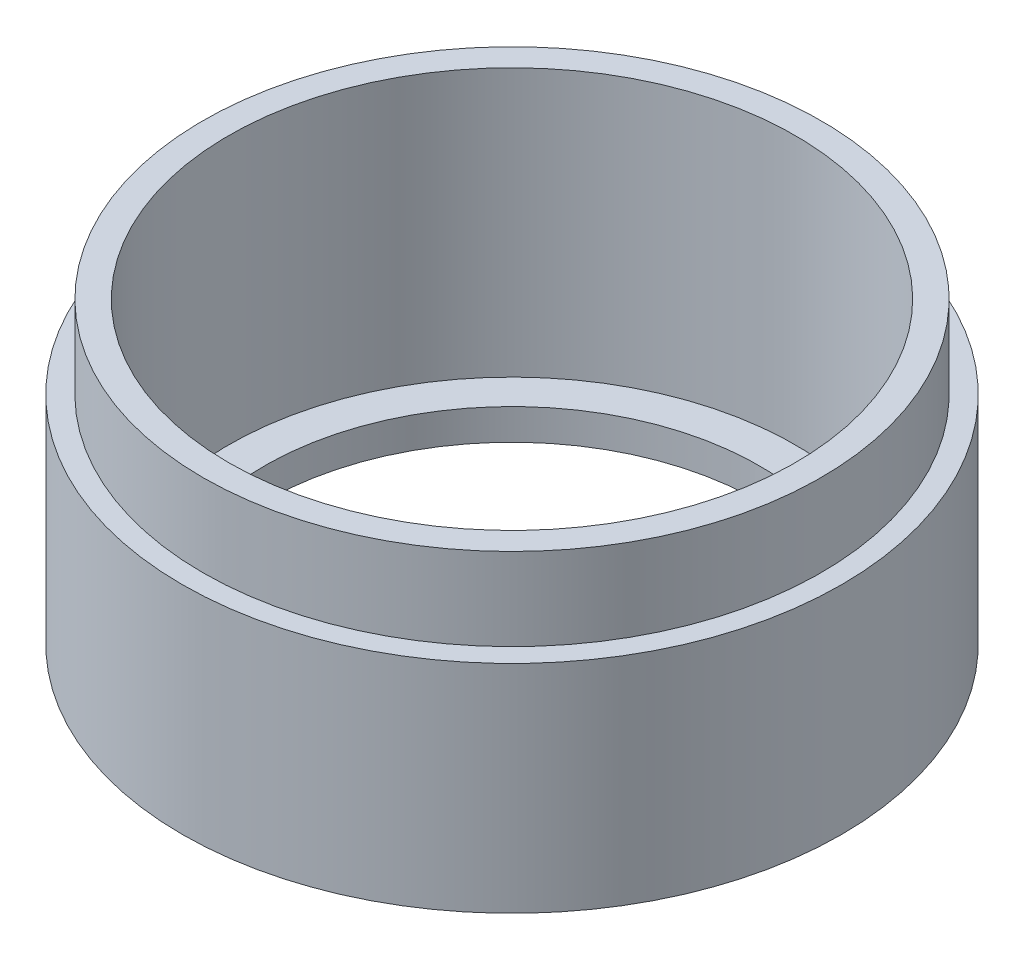
SolidWorks part; units mm, degrees
ref_plane "Спереди" through (0, 0, 0) normal (0, 0, 1) x (1, 0, 0)
ref_plane "Сверху" through (0, 0, 0) normal (0, 1, 0) x (1, 0, 0)
ref_plane "Справа" through (0, 0, 0) normal (1, 0, 0) x (0, 0, -1)
sketch "Эскиз1" plane through (0, 0, 0) normal (0, 0, 1) x (1, 0, 0)
  line L0 (0, 46.0252) -> (0, -56.0671) construction
  line L1 (27.5, -20.4944) -> (30, -20.4944)
  line L2 (32, -28.4944) -> (32, -49.4944)
  line L3 (24, -46.4944) -> (24, -49.4944)
  line L4 (30, -20.4944) -> (30, -28.4944)
  line L5 (32, -49.4944) -> (24, -49.4944)
  line L6 (24, -46.4944) -> (27.5, -46.4944)
  line L7 (27.5, -46.4944) -> (27.5, -20.4944)
  line L8 (30, -28.4944) -> (32, -28.4944)
  dimension "D1" = 27.5
  dimension "D2" = 32
  dimension "D3" = 3
  dimension "D4" = 26
  dimension "D5" = 24
  dimension "D6" = 8
  dimension "D7" = 30
revolve "Повернуть1" add sketch "Эскиз1" angle 360 about L0
